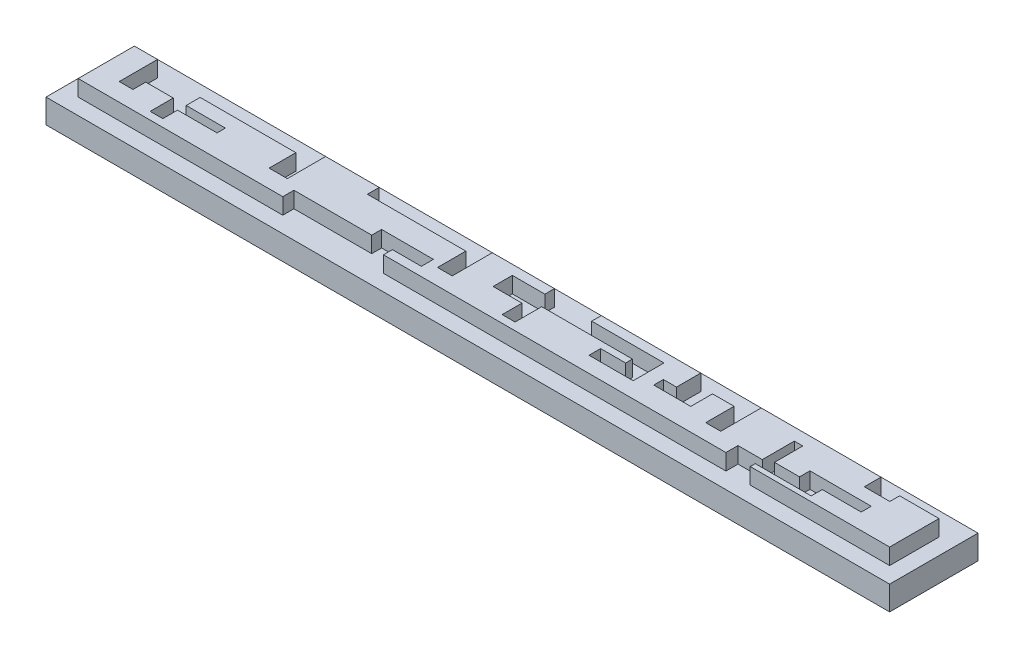
SolidWorks part; units mm, degrees
ref_plane "前视基准面" through (0, 0, 0) normal (0, 0, 1) x (1, 0, 0)
ref_plane "上视基准面" through (0, 0, 0) normal (0, 1, 0) x (1, 0, 0)
ref_plane "右视基准面" through (0, 0, 0) normal (1, 0, 0) x (0, 0, -1)
sketch "草图1" plane through (0, 0, 0) normal (0, 1, 0) x (1, 0, 0)
  line L1 (0, 0) -> (52.5, 0)
  line L2 (0, 0) -> (0, -5.5)
  line L3 (0, -5.5) -> (52.5, -5.5)
  line L4 (52.5, 0) -> (52.5, -5.5)
  dimension "D1" = 52.5
  dimension "D2" = 5.5
extrude "凸台-拉伸1" add sketch "草图1" along normal blind 1.5
sketch "草图2" plane through (0, 1.5, 0) normal (0, 1, 0) x (1, 0, 0)
  line L0 (0, -2.75) -> (1, -2.75) construction
  line L1 (1, -1) -> (51.5, -1)
  line L2 (1, -1) -> (1, -4.5)
  line L3 (1, -4.5) -> (51.5, -4.5)
  line L4 (51.5, -1) -> (51.5, -4.5)
  line L5 (0, 0) -> (0, -5.5) construction
  line L6 (26.25, -1) -> (26.25, 0) construction
  line L7 (52.5, 0) -> (0, 0) construction
  dimension "D1" = 3.5
  dimension "D2" = 50.5
extrude "凸台-拉伸2" add sketch "草图2" along normal blind 1
sketch "草图3" plane through (0, 2.5, 0) normal (0, 1, 0) x (1, 0, 0)
  line L0 (2.4413, -1) -> (2.4413, -3.3858)
  line L1 (51.5, -1) -> (1, -1) construction
  line L2 (2.4413, -3.3858) -> (3.2978, -3.3858)
  line L3 (3.2978, -3.3858) -> (3.2978, -2.5902)
  line L4 (3.2978, -2.5902) -> (5.0108, -2.5902)
  line L5 (5.0108, -2.5902) -> (5.0108, -4.0282)
  line L6 (5.0108, -4.0282) -> (5.7975, -4.0282)
  line L7 (5.7975, -4.0282) -> (5.7975, -3.1105)
  line L8 (5.7975, -3.1105) -> (8.2533, -3.1105)
  line L9 (8.2533, -3.1105) -> (8.2533, -2.5902)
  line L10 (8.2533, -2.5902) -> (5.8136, -2.5902)
  line L11 (5.8136, -2.5902) -> (5.8136, -1.722)
  line L12 (5.8136, -1.722) -> (11.7711, -1.722)
  line L13 (11.7711, -1.722) -> (11.7711, -3.3858)
  line L14 (11.7711, -3.3858) -> (12.9042, -3.3858)
  line L15 (12.9042, -3.3858) -> (12.9042, -1)
  line L16 (12.9042, -1) -> (2.4413, -1)
  line L17 (13.7349, -4.5) -> (13.7349, -3.8063)
  line L18 (1, -4.5) -> (51.5, -4.5) construction
  line L19 (13.7349, -3.8063) -> (18.5772, -3.8063)
  line L20 (18.5772, -3.8063) -> (18.5772, -3.1911)
  line L21 (18.5772, -3.1911) -> (21.8009, -3.1911)
  line L22 (21.8009, -3.1911) -> (21.8009, -3.9429)
  line L23 (21.8009, -3.9429) -> (20.0009, -3.9429)
  line L24 (20.0009, -3.9429) -> (20.0009, -4.5)
  line L25 (1, -4.5) -> (51.5, -4.5) construction
  line L26 (20.0009, -4.5) -> (13.7349, -4.5)
  line L27 (16.2376, -1) -> (16.2376, -1.7377)
  line L28 (51.5, -1) -> (1, -1) construction
  line L29 (16.2376, -1.7377) -> (22.3653, -1.7377)
  line L30 (22.3653, -1.7377) -> (22.3653, -3.5)
  line L31 (22.3653, -3.5) -> (23.2775, -3.5)
  line L32 (23.2775, -3.5) -> (23.2775, -1)
  line L33 (23.2775, -1) -> (16.2376, -1)
  line L34 (25.1193, -1.5983) -> (25.1193, -2.7963)
  line L35 (25.1193, -2.7963) -> (26.9163, -2.7963)
  line L36 (26.9163, -2.7963) -> (26.9163, -4.0282)
  line L37 (26.9163, -4.0282) -> (27.7218, -4.0282)
  line L38 (27.7218, -4.0282) -> (27.7218, -2.3712)
  line L39 (27.7218, -2.3712) -> (33.3672, -2.3712)
  line L40 (33.3672, -2.3712) -> (33.3672, -2.7963)
  line L41 (33.3672, -2.7963) -> (31.8115, -2.7963)
  line L42 (31.8115, -2.7963) -> (31.8115, -3.5192)
  line L43 (31.8115, -3.5192) -> (34.5586, -3.5192)
  line L44 (34.5586, -3.5192) -> (34.5586, -1.5983)
  line L45 (34.5586, -1.5983) -> (30.0558, -1.5983)
  line L46 (30.0558, -1.5983) -> (30.0558, -1)
  line L47 (30.0558, -1) -> (27.1435, -1)
  line L48 (27.1435, -1) -> (27.1435, -1.5983)
  line L49 (27.1435, -1.5983) -> (25.1193, -1.5983)
  line L50 (36.2472, -1) -> (36.2472, -2.5102)
  line L51 (36.2472, -2.5102) -> (35.4309, -2.5102)
  line L52 (35.4309, -2.5102) -> (35.4309, -3.1105)
  line L53 (35.4309, -3.1105) -> (37.734, -3.1105)
  line L54 (37.734, -3.1105) -> (37.734, -1.7551)
  line L55 (37.734, -1.7551) -> (39.075, -1.7551)
  line L56 (39.075, -1.7551) -> (39.075, -3.5192)
  line L57 (39.075, -3.5192) -> (40.0079, -3.5192)
  line L58 (40.0079, -3.5192) -> (40.0079, -1.4281)
  line L59 (40.0079, -1.4281) -> (40.0079, -1)
  line L60 (40.0079, -1) -> (36.2472, -1)
  line L61 (41.3131, -4.5) -> (41.3131, -3.7492)
  line L62 (41.3131, -3.7492) -> (42.8254, -3.7492)
  line L63 (42.8254, -3.7492) -> (42.8254, -1.7551)
  line L64 (42.8254, -1.7551) -> (43.3535, -1.7551)
  line L65 (43.3535, -1.7551) -> (43.3535, -3.5192)
  line L66 (43.3535, -3.5192) -> (44.9137, -3.5192)
  line L67 (44.9137, -3.5192) -> (44.9137, -2.873)
  line L68 (44.9137, -2.873) -> (48.7304, -2.873)
  line L69 (48.7304, -2.873) -> (48.7304, -3.5)
  line L70 (48.7304, -3.5) -> (46.306, -3.5)
  line L71 (46.306, -3.5) -> (46.306, -4.185)
  line L72 (46.306, -4.185) -> (42.8254, -4.185)
  line L73 (42.8254, -4.185) -> (42.8254, -4.5)
  line L74 (41.3131, -4.5) -> (42.8254, -4.5)
  line L75 (47.4645, -1) -> (47.4645, -2.0394)
  line L76 (47.4645, -2.0394) -> (49.05, -2.0394)
  line L77 (49.05, -2.0394) -> (49.05, -1.4281)
  line L78 (49.05, -1.4281) -> (51.5, -1.4281)
  line L79 (51.5, -4.5) -> (51.5, -1) construction
  line L80 (51.5, -1.4281) -> (51.5, -1)
  line L81 (51.5, -4.5) -> (51.5, -1) construction
  line L82 (51.5, -1) -> (47.4645, -1)
extrude "切除-拉伸1" cut sketch "草图3" against normal up to surface (1 mm away) up to face at (26.25, 1.5, 2.75)
